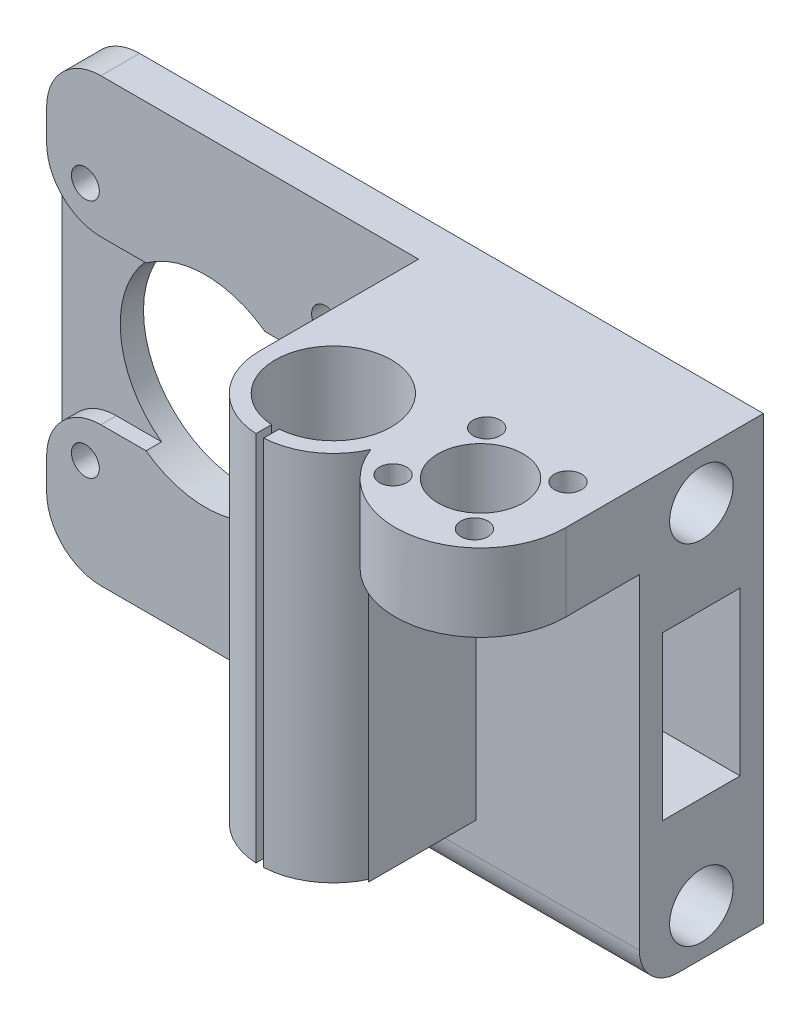
SolidWorks part; units mm, degrees
material "ABS"
ref_plane "Front Plane" through (0, 0, 0) normal (0, 0, 1) x (1, 0, 0)
ref_plane "Top Plane" through (0, 0, 0) normal (0, 1, 0) x (1, 0, 0)
ref_plane "Right Plane" through (0, 0, 0) normal (1, 0, 0) x (0, 0, -1)
sketch "Sketch2" plane through (0, 0, 0) normal (0, 1, 0) x (1, 0, 0)
  line L0 (0, 0) -> (0, -5)
  line L1 (0, -5) -> (48, -5)
  line L2 (48, -5) -> (48, -25.5)
  line L3 (57.5, -25.5) -> (48, -25.5) construction
  line L4 (87.5, -25.5) -> (87.5, 0)
  line L5 (87.5, 0) -> (0, 0)
  line L6 (57.5, -25.5) -> (76.5, -25.5) construction
  line L7 (66.1908, -29.3367) -> (66.1908, -25.5) construction
  line L8 (71.2515, -19.4623) -> (81.7485, -31.5377) construction
  line L9 (82.5377, -20.2515) -> (70.4623, -30.7485) construction
  line L10 (57.5, -25.5) -> (57.5, -34.9868) construction
  line L11 (57, -34.9868) -> (57.5, -34.9868) construction
  line L12 (57.5, -34.9868) -> (58, -34.9868) construction
  line L13 (57, -34.9868) -> (57, -32.9833)
  line L15 (58, -34.9868) -> (58, -32.9833)
  arc A0 (48, -25.5) -> (57, -34.9868) centre (57.5, -25.5) ccw
  circle A1 centre (76.5, -25.5) radius 5.5
  arc A2 (58, -32.9833) -> (57, -32.9833) centre (57.5, -25.5) ccw
  arc A3 (66.1908, -29.3367) -> (87.5, -25.5) centre (76.5, -25.5) ccw
  circle A4 centre (76.5, -25.5) radius 8 construction
  circle A5 centre (70.4623, -30.7485) radius 1.75
  circle A6 centre (82.5377, -20.2515) radius 1.75
  circle A7 centre (71.2515, -19.4623) radius 1.75
  circle A8 centre (81.7485, -31.5377) radius 1.75
  arc A9 (58, -34.9868) -> (66.1908, -29.3367) centre (57.5, -25.5) ccw
  dimension "D5" = 2
  dimension "D8" = 11
  dimension "D9" = 15
  dimension "D10" = 16
  dimension "D1" = 5.5
  dimension "D12" = 41
  dimension "D13" = 3.5
  dimension "D2" = 48
  dimension "D3" = 5
  dimension "D4" = 20.5
  dimension "D7" = 19
  dimension "D14" = 1
extrude "Boss-Extrude1" add sketch "Sketch2" along normal mid plane 57 contours L15 A9 A3 L4 L5 L0 L1 L2 A0 L13 A2 A1 A5 A6 A7 A8
sketch "Sketch3" plane through (0, 0, 0) normal (0, 0, 1) x (1, 0, 0)
  line L0 (0, 0) -> (88, 0) construction
  line L1 (66.4, 18.5) -> (88, 18.5)
  line L2 (66.4, 18.5) -> (66.4, -19.5)
  line L4 (88, 18.5) -> (88, -28.5)
  line L8 (48, -19.5) -> (66.4, -19.5)
  line L9 (48, -19.5) -> (48, -28.5)
  line L10 (48, -28.5) -> (88, -28.5)
  dimension "D4" = 47
  dimension "D1" = 88
  dimension "D2" = 18.5
  dimension "D3" = 21.6
  dimension "D5" = 9
  dimension "D6" = 18.4
extrude "Cut-Extrude1" cut sketch "Sketch3" along normal through all from offset 16
sketch "Sketch4" plane through (0, 0, 0) normal (0, 0, 1) x (1, 0, 0)
  line L0 (5, 15.5) -> (36, 15.5) construction
  line L1 (36, 15.5) -> (36, -15.5) construction
  line L2 (36, -15.5) -> (5, -15.5) construction
  line L3 (5, -15.5) -> (5, 15.5) construction
  line L4 (5, -15.5) -> (36, 15.5) construction
  circle A0 centre (5, 15.5) radius 1.8
  circle A1 centre (36, 15.5) radius 1.8
  circle A2 centre (5, -15.5) radius 1.8
  circle A3 centre (36, -15.5) radius 1.8
  circle A4 centre (20.5, 0) radius 13
  dimension "D1" = 31
  dimension "D2" = 3.6
  dimension "D5" = 26
  dimension "D3" = 15.5
  dimension "D4" = 5
extrude "Holes-for-motor" cut sketch "Sketch4" along normal through all
sketch "Sketch6" plane through (0, 0, 0) normal (1, 0, 0) x (0, 0, -1)
  line L0 (-3, 0) -> (0, 0) construction
  line L1 (-13, 10.5) -> (-3, 10.5)
  line L2 (-13, 10.5) -> (-13, -10.5)
  line L3 (-13, -10.5) -> (-3, -10.5)
  line L4 (-3, 10.5) -> (-3, -10.5)
  dimension "D1" = 10
  dimension "D2" = 21
  dimension "D3" = 3
extrude "Cut-Extrude3" cut sketch "Sketch6" along normal through all
sketch "Sketch11" plane through (87.5, 0, 0) normal (1, 0, 0) x (0, 0, -1)
  line L0 (-8, 0) -> (-8, 22.5) construction
  line L1 (-8, -22.5) -> (-8, 0) construction
  line L2 (0, 0) -> (-8, 0) construction
  line L3 (-8, -22.5) -> (-8, -28.5) construction
  line L5 (-16, -28.5) -> (0, -28.5) construction
  circle A0 centre (-8, -22.5) radius 4.1
  circle A1 centre (-8, 22.5) radius 4.1
  dimension "D1" = 45
  dimension "D2" = 8.2
extrude "Cut-Extrude7" cut sketch "Sketch11" against normal blind 21.691
fillet "Fillet2" radius 5 1 edges at (67.75, -28.5, 16)
fillet "Fillet3" radius 7 4 edges at (0, -28.5, 2.5) (0, 28.5, 2.5) (0, -10.5, 4) (0, 10.5, 4)
